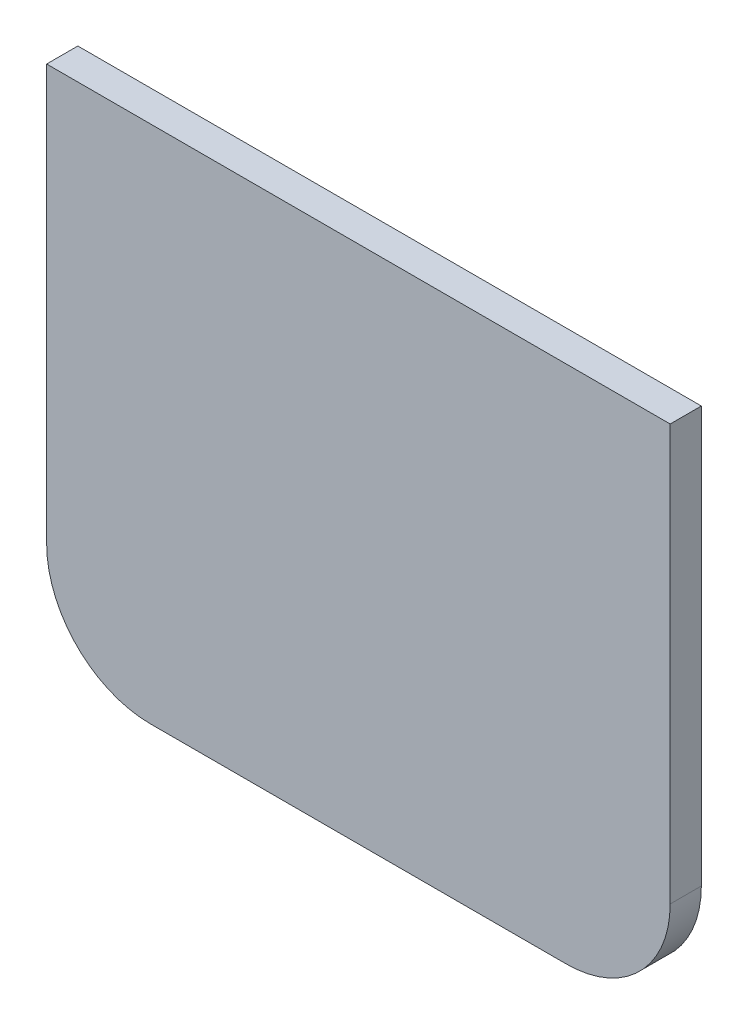
SolidWorks part; units mm, degrees
ref_plane "Plan de face" through (0, 0, 0) normal (0, 0, 1) x (1, 0, 0)
ref_plane "Plan de dessus" through (0, 0, 0) normal (0, 1, 0) x (1, 0, 0)
ref_plane "Plan de droite" through (0, 0, 0) normal (1, 0, 0) x (0, 0, -1)
sketch "Esquisse1" plane through (0, 0, 0) normal (0, 0, 1) x (1, 0, 0)
  line L1 (-100, -125) -> (100, -125)
  line L2 (-150, -75) -> (-150, 125)
  line L3 (-150, 125) -> (150, 125)
  line L4 (150, -75) -> (150, 125)
  line L5 (-150, -125) -> (150, 125) construction
  line L6 (-150, 125) -> (150, -125) construction
  arc A0 (-100, -125) -> (-150, -75) centre (-100, -75) cw
  arc A1 (100, -125) -> (150, -75) centre (100, -75) ccw
  point P0 (0, 0)
  dimension "D3" = 50
  dimension "D1" = 300
  dimension "D2" = 250
extrude "Boss.-Extru.1" add sketch "Esquisse1" along normal blind 15
